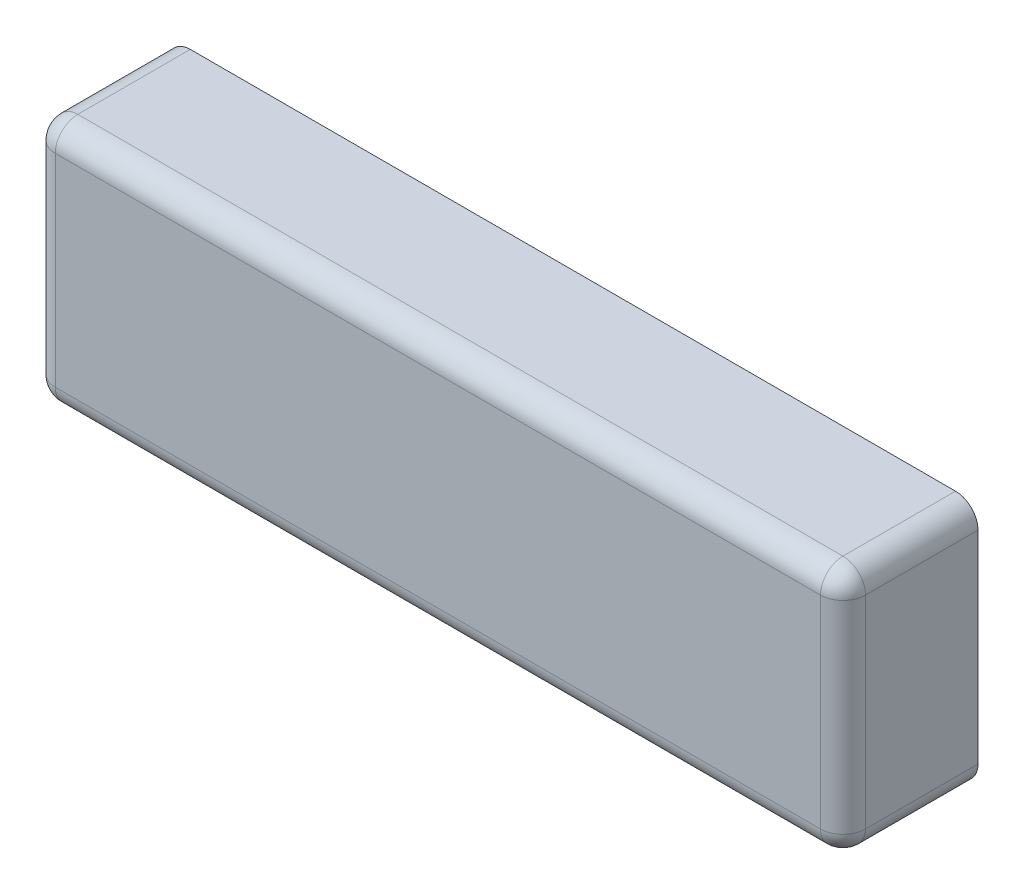
SolidWorks part; units mm, degrees
material "Silicon Dioxide"
ref_plane "Front Plane" through (0, 0, 0) normal (0, 0, 1) x (1, 0, 0)
ref_plane "Top Plane" through (0, 0, 0) normal (0, 1, 0) x (1, 0, 0)
ref_plane "Right Plane" through (0, 0, 0) normal (1, 0, 0) x (0, 0, -1)
sketch "Sketch1" plane through (0, 0, 0) normal (0, 0, 1) x (1, 0, 0)
  line L1 (-75.6362, 48.0134) -> (104.3638, 48.0134)
  line L2 (-75.6362, 48.0134) -> (-75.6362, -6.9866)
  line L3 (-75.6362, -6.9866) -> (104.3638, -6.9866)
  line L4 (104.3638, 48.0134) -> (104.3638, -6.9866)
  dimension "D1" = 180
  dimension "D2" = 55
extrude "Boss-Extrude1" add sketch "Sketch1" along normal blind 30
fillet "Fillet1" radius 5 8 edges at (-75.6362, -6.9866, 15) (104.3638, -6.9866, 15) (14.3638, -6.9866, 30) (104.3638, 20.5134, 30) (104.3638, 48.0134, 15) (-75.6362, 20.5134, 30) (-75.6362, 48.0134, 15) (14.3638, 48.0134, 30)
